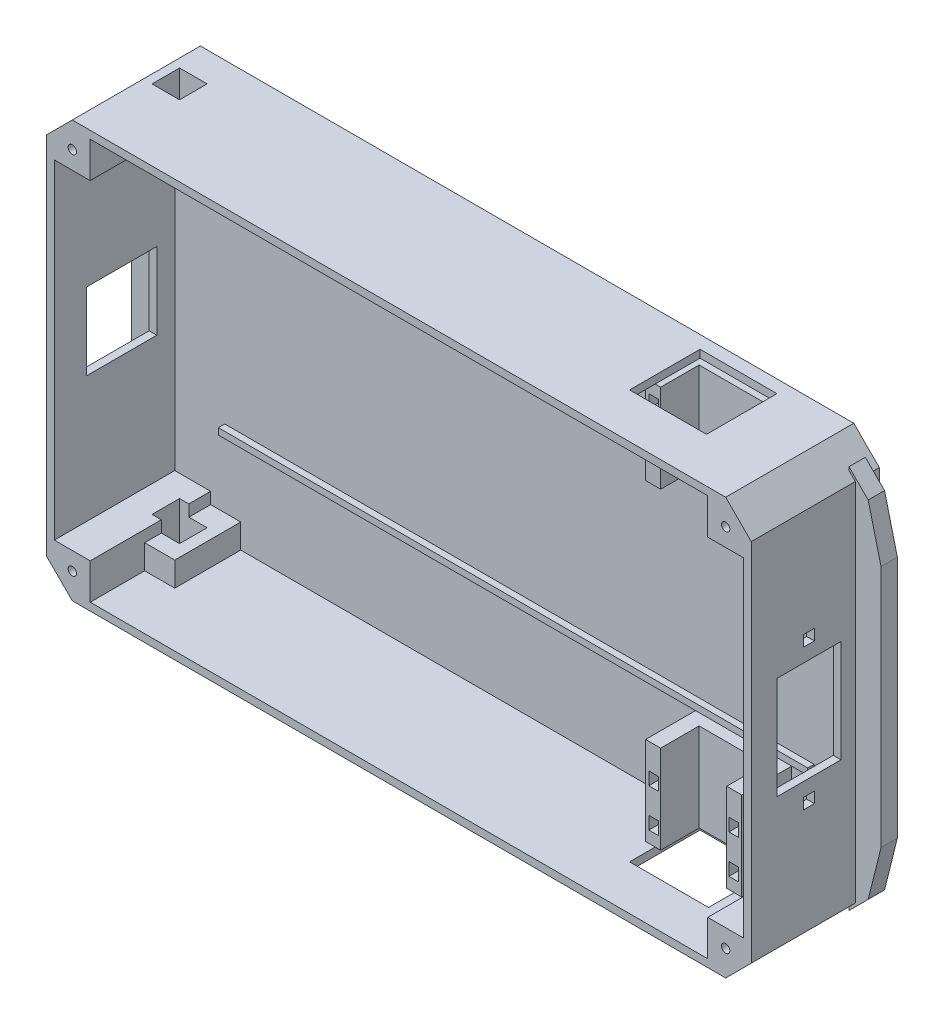
SolidWorks part; units mm, degrees
ref_plane "Front Plane" through (0, 0, 0) normal (0, 0, 1) x (1, 0, 0)
ref_plane "Top Plane" through (0, 0, 0) normal (0, 1, 0) x (1, 0, 0)
ref_plane "Right Plane" through (0, 0, 0) normal (1, 0, 0) x (0, 0, -1)
sketch "Sketch1" plane through (0, 0, 0) normal (0, 0, 1) x (1, 0, 0)
  line L0 (-102, -65) -> (102, -65)
  line L1 (102, -65) -> (110, -57)
  line L2 (110, -57) -> (110, 57)
  line L3 (110, 57) -> (102, 65)
  line L4 (102, 65) -> (-102, 65)
  line L5 (-102, 65) -> (-110, 57)
  line L6 (-110, 57) -> (-110, -57)
  line L7 (-110, -57) -> (-102, -65)
extrude "Faceted_Floor_220x130" add sketch "Sketch1" along normal blind 2.4 from offset 0
sketch "Sketch2" plane through (0, 0, 0) normal (0, 0, 1) x (1, 0, 0)
  line L0 (-102, -65) -> (102, -65)
  line L1 (102, -65) -> (110, -57)
  line L2 (110, -57) -> (110, 57)
  line L3 (110, 57) -> (102, 65)
  line L4 (102, 65) -> (-102, 65)
  line L5 (-102, 65) -> (-110, 57)
  line L6 (-110, 57) -> (-110, -57)
  line L7 (-110, -57) -> (-102, -65)
  line L8 (-102, -62.6) -> (102, -62.6)
  line L9 (102, -62.6) -> (107.6, -57)
  line L10 (107.6, -57) -> (107.6, 57)
  line L11 (107.6, 57) -> (102, 62.6)
  line L12 (102, 62.6) -> (-102, 62.6)
  line L13 (-102, 62.6) -> (-107.6, 57)
  line L14 (-107.6, 57) -> (-107.6, -57)
  line L15 (-107.6, -57) -> (-102, -62.6)
extrude "Faceted_Hollow_Walls_2p4" add sketch "Sketch2" along normal blind 37.6 from offset 2.4
sketch "Sketch3" plane through (0, 0, 0) normal (0, 0, 1) x (1, 0, 0)
  line L1 (-107.6, -62.6) -> (-96.4, -62.6)
  line L2 (-107.6, -62.6) -> (-107.6, -51.4)
  line L3 (-107.6, -51.4) -> (-96.4, -51.4)
  line L4 (-96.4, -62.6) -> (-96.4, -51.4)
extrude "Lid_Post_-1_-1" add sketch "Sketch3" along normal blind 37.6 from offset 2.4
sketch "Sketch4" plane through (0, 0, 0) normal (0, 0, 1) x (1, 0, 0)
  circle A0 centre (-102, -57) radius 1.3
extrude "M3_Pilot_-1_-1" cut sketch "Sketch4" along normal blind 14 from offset 27
sketch "Sketch5" plane through (0, 0, 0) normal (0, 0, 1) x (1, 0, 0)
  line L0 (-107.6, 57) -> (-107.6, -51.4) construction
  line L1 (-107.6, 51.4) -> (-96.4, 51.4)
  line L2 (-107.6, 51.4) -> (-107.6, 62.6)
  line L3 (-107.6, 62.6) -> (-96.4, 62.6)
  line L4 (-96.4, 51.4) -> (-96.4, 62.6)
  line L5 (102, 62.6) -> (-102, 62.6) construction
extrude "Lid_Post_-1_1" add sketch "Sketch5" along normal blind 37.6 from offset 2.4
sketch "Sketch6" plane through (0, 0, 0) normal (0, 0, 1) x (1, 0, 0)
  circle A0 centre (-102, 57) radius 1.3
extrude "M3_Pilot_-1_1" cut sketch "Sketch6" along normal blind 14 from offset 27
sketch "Sketch7" plane through (0, 0, 0) normal (0, 0, 1) x (1, 0, 0)
  line L0 (-96.4, -62.6) -> (102, -62.6) construction
  line L1 (96.4, -62.6) -> (107.6, -62.6)
  line L2 (96.4, -62.6) -> (96.4, -51.4)
  line L3 (96.4, -51.4) -> (107.6, -51.4)
  line L4 (107.6, -62.6) -> (107.6, -51.4)
  line L5 (107.6, -57) -> (107.6, 57) construction
extrude "Lid_Post_1_-1" add sketch "Sketch7" along normal blind 37.6 from offset 2.4
sketch "Sketch8" plane through (0, 0, 0) normal (0, 0, 1) x (1, 0, 0)
  circle A0 centre (102, -57) radius 1.3
extrude "M3_Pilot_1_-1" cut sketch "Sketch8" along normal blind 14 from offset 27
sketch "Sketch9" plane through (0, 0, 0) normal (0, 0, 1) x (1, 0, 0)
  line L1 (96.4, 51.4) -> (107.6, 51.4)
  line L2 (96.4, 51.4) -> (96.4, 62.6)
  line L3 (96.4, 62.6) -> (107.6, 62.6)
  line L4 (107.6, 51.4) -> (107.6, 62.6)
extrude "Lid_Post_1_1" add sketch "Sketch9" along normal blind 37.6 from offset 2.4
sketch "Sketch10" plane through (0, 0, 0) normal (0, 0, 1) x (1, 0, 0)
  circle A0 centre (102, 57) radius 1.3
extrude "M3_Pilot_1_1" cut sketch "Sketch10" along normal blind 14 from offset 27
sketch "Sketch11" plane through (0, 0, 0) normal (0, 0, 1) x (1, 0, 0)
  line L0 (-102, -65) -> (102, -65) construction
  line L1 (55, -65) -> (85, -65)
  line L2 (55, -65) -> (55, -35)
  line L3 (55, -35) -> (85, -35)
  line L4 (85, -65) -> (85, -35)
extrude "Motor_Saddle_Base_-1" add sketch "Sketch11" along normal blind 3.6 from offset 2.4
sketch "Sketch12" plane through (0, 0, 0) normal (0, 0, 1) x (1, 0, 0)
  line L0 (-102, -65) -> (102, -65) construction
  line L1 (55, -65) -> (59.7, -65)
  line L2 (55, -65) -> (55, -35)
  line L3 (55, -35) -> (59.7, -35)
  line L4 (59.7, -65) -> (59.7, -35)
  line L5 (85, -35) -> (55, -35) construction
extrude "Motor_Guide_A_-1" add sketch "Sketch12" along normal blind 12 from offset 6
sketch "Sketch13" plane through (0, 0, 0) normal (0, 0, 1) x (1, 0, 0)
  line L0 (-102, -65) -> (102, -65) construction
  line L1 (80.3, -65) -> (85, -65)
  line L2 (80.3, -65) -> (80.3, -35)
  line L3 (80.3, -35) -> (85, -35)
  line L4 (85, -65) -> (85, -35)
extrude "Motor_Guide_B_-1" add sketch "Sketch13" along normal blind 12 from offset 6
sketch "Sketch14" plane through (0, 0, 0) normal (0, 0, 1) x (1, 0, 0)
  line L1 (56, -47) -> (59, -47)
  line L2 (56, -47) -> (56, -43)
  line L3 (56, -43) -> (59, -43)
  line L4 (59, -47) -> (59, -43)
extrude "TieSlot_-1_56_43" cut sketch "Sketch14" along normal blind 19 from offset 0.1
sketch "Sketch15" plane through (0, 0, 0) normal (0, 0, 1) x (1, 0, 0)
  line L1 (81, -47) -> (84, -47)
  line L2 (81, -47) -> (81, -43)
  line L3 (81, -43) -> (84, -43)
  line L4 (84, -47) -> (84, -43)
extrude "TieSlot_-1_81_43" cut sketch "Sketch15" along normal blind 19 from offset 0.1
sketch "Sketch16" plane through (0, 0, 0) normal (0, 0, 1) x (1, 0, 0)
  line L1 (56, -59) -> (59, -59)
  line L2 (56, -59) -> (56, -55)
  line L3 (56, -55) -> (59, -55)
  line L4 (59, -59) -> (59, -55)
extrude "TieSlot_-1_56_55" cut sketch "Sketch16" along normal blind 19 from offset 0.1
sketch "Sketch17" plane through (0, 0, 0) normal (0, 0, 1) x (1, 0, 0)
  line L1 (81, -59) -> (84, -59)
  line L2 (81, -59) -> (81, -55)
  line L3 (81, -55) -> (84, -55)
  line L4 (84, -59) -> (84, -55)
extrude "TieSlot_-1_81_55" cut sketch "Sketch17" along normal blind 19 from offset 0.1
sketch "Sketch18" plane through (0, 0, 0) normal (0, 0, 1) x (1, 0, 0)
  line L0 (85, -62.6) -> (80.3, -62.6) construction
  line L1 (58, -66) -> (82.65, -66)
  line L2 (58, -66) -> (58, -62.6)
  line L3 (58, -62.6) -> (82.65, -62.6)
  line L4 (82.65, -66) -> (82.65, -62.6)
extrude "Motor_Side_Window_-1" cut sketch "Sketch18" along normal blind 22 from offset 4
sketch "Sketch19" plane through (0, 0, 0) normal (0, 0, 1) x (1, 0, 0)
  line L1 (-103, -65) -> (-87, -65)
  line L2 (-103, -65) -> (-103, -55)
  line L3 (-103, -55) -> (-87, -55)
  line L4 (-87, -65) -> (-87, -55)
extrude "Rear_Axle_Support_-1" add sketch "Sketch19" along normal blind 20.6 from offset 2.4
sketch "Sketch20" plane through (0, 0, 0) normal (0, 0, 1) x (1, 0, 0)
  line L1 (-99.3, -66) -> (-90.7, -66)
  line L2 (-99.3, -66) -> (-99.3, -51)
  line L3 (-99.3, -51) -> (-90.7, -51)
  line L4 (-90.7, -66) -> (-90.7, -51)
extrude "Rear_Printed_Axle_Clearance_8p6-1" cut sketch "Sketch20" along normal blind 8.6 from offset 9.2
sketch "Sketch21" plane through (0, 0, 0) normal (0, 0, 1) x (1, 0, 0)
  line L0 (102, 65) -> (-102, 65) construction
  line L1 (55, 35) -> (85, 35)
  line L2 (55, 35) -> (55, 65)
  line L3 (55, 65) -> (85, 65)
  line L4 (85, 35) -> (85, 65)
extrude "Motor_Saddle_Base_1" add sketch "Sketch21" along normal blind 3.6 from offset 2.4
sketch "Sketch22" plane through (0, 0, 0) normal (0, 0, 1) x (1, 0, 0)
  line L0 (102, 65) -> (-102, 65) construction
  line L1 (55, 35) -> (59.7, 35)
  line L2 (55, 35) -> (55, 65)
  line L3 (55, 65) -> (59.7, 65)
  line L4 (59.7, 35) -> (59.7, 65)
extrude "Motor_Guide_A_1" add sketch "Sketch22" along normal blind 12 from offset 6
sketch "Sketch23" plane through (0, 0, 0) normal (0, 0, 1) x (1, 0, 0)
  line L0 (59.7, 35) -> (85, 35) construction
  line L1 (80.3, 35) -> (85, 35)
  line L2 (80.3, 35) -> (80.3, 65)
  line L3 (80.3, 65) -> (85, 65)
  line L4 (85, 35) -> (85, 65)
  line L5 (102, 65) -> (-102, 65) construction
extrude "Motor_Guide_B_1" add sketch "Sketch23" along normal blind 12 from offset 6
sketch "Sketch24" plane through (0, 0, 0) normal (0, 0, 1) x (1, 0, 0)
  line L1 (56, 43) -> (59, 43)
  line L2 (56, 43) -> (56, 47)
  line L3 (56, 47) -> (59, 47)
  line L4 (59, 43) -> (59, 47)
extrude "TieSlot_1_56_43" cut sketch "Sketch24" along normal blind 19 from offset 0.1
sketch "Sketch25" plane through (0, 0, 0) normal (0, 0, 1) x (1, 0, 0)
  line L1 (81, 43) -> (84, 43)
  line L2 (81, 43) -> (81, 47)
  line L3 (81, 47) -> (84, 47)
  line L4 (84, 43) -> (84, 47)
extrude "TieSlot_1_81_43" cut sketch "Sketch25" along normal blind 19 from offset 0.1
sketch "Sketch26" plane through (0, 0, 0) normal (0, 0, 1) x (1, 0, 0)
  line L1 (56, 55) -> (59, 55)
  line L2 (56, 55) -> (56, 59)
  line L3 (56, 59) -> (59, 59)
  line L4 (59, 55) -> (59, 59)
extrude "TieSlot_1_56_55" cut sketch "Sketch26" along normal blind 19 from offset 0.1
sketch "Sketch27" plane through (0, 0, 0) normal (0, 0, 1) x (1, 0, 0)
  line L1 (81, 55) -> (84, 55)
  line L2 (81, 55) -> (81, 59)
  line L3 (81, 59) -> (84, 59)
  line L4 (84, 55) -> (84, 59)
extrude "TieSlot_1_81_55" cut sketch "Sketch27" along normal blind 19 from offset 0.1
sketch "Sketch28" plane through (0, 0, 0) normal (0, 0, 1) x (1, 0, 0)
  line L0 (96.4, 62.6) -> (-96.4, 62.6) construction
  line L1 (58, 62.6) -> (82, 62.6)
  line L2 (58, 62.6) -> (58, 66)
  line L3 (58, 66) -> (82, 66)
  line L4 (82, 62.6) -> (82, 66)
extrude "Motor_Side_Window_1" cut sketch "Sketch28" along normal blind 22 from offset 4
sketch "Sketch29" plane through (0, 0, 0) normal (0, 0, 1) x (1, 0, 0)
  line L0 (102, 65) -> (-102, 65) construction
  line L1 (-103, 55) -> (-87, 55)
  line L2 (-103, 55) -> (-103, 65)
  line L3 (-103, 65) -> (-87, 65)
  line L4 (-87, 55) -> (-87, 65)
extrude "Rear_Axle_Support_1" add sketch "Sketch29" along normal blind 20.6 from offset 2.4
sketch "Sketch30" plane through (0, 0, 0) normal (0, 0, 1) x (1, 0, 0)
  line L0 (-107.6, 51.4) -> (-96.4, 51.4) construction
  line L1 (-99.3, 51.4) -> (-90.7, 51.4)
  line L2 (-99.3, 51.4) -> (-99.3, 66)
  line L3 (-99.3, 66) -> (-90.7, 66)
  line L4 (-90.7, 51.4) -> (-90.7, 66)
extrude "Rear_Printed_Axle_Clearance_8p61" cut sketch "Sketch30" along normal blind 8.6 from offset 9.2
sketch "Sketch31" plane through (0, 0, 0) normal (0, 0, 1) x (1, 0, 0)
  line L0 (-107.6, 51.4) -> (-107.6, -51.4) construction
  line L1 (-111, -12) -> (-107.6, -12)
  line L2 (-111, -12) -> (-111, 12)
  line L3 (-111, 12) -> (-107.6, 12)
  line L4 (-107.6, -12) -> (-107.6, 12)
extrude "Rear_USB_Access_24x22" cut sketch "Sketch31" along normal blind 22 from offset 8
sketch "Sketch32" plane through (0, 0, 0) normal (0, 0, 1) x (1, 0, 0)
  line L0 (107.6, -51.4) -> (107.6, 51.4) construction
  line L1 (107.6, -16) -> (111, -16)
  line L2 (107.6, -16) -> (107.6, 16)
  line L3 (107.6, 16) -> (111, 16)
  line L4 (111, -16) -> (111, 16)
extrude "Front_ToF_Window_32x20" cut sketch "Sketch32" along normal blind 20 from offset 12
sketch "Sketch33" plane through (0, 0, 0) normal (0, 0, 1) x (1, 0, 0)
  line L0 (107.6, -51.4) -> (107.6, 51.4) construction
  line L1 (107.6, -23.7) -> (111, -23.7)
  line L2 (107.6, -23.7) -> (107.6, -20.3)
  line L3 (107.6, -20.3) -> (111, -20.3)
  line L4 (111, -23.7) -> (111, -20.3)
extrude "ToF_M3_Clearance_-1" cut sketch "Sketch33" along normal blind 3.4 from offset 20.3
sketch "Sketch34" plane through (0, 0, 0) normal (0, 0, 1) x (1, 0, 0)
  line L0 (107.6, -51.4) -> (107.6, 51.4) construction
  line L1 (107.6, 20.3) -> (111, 20.3)
  line L2 (107.6, 20.3) -> (107.6, 23.7)
  line L3 (107.6, 23.7) -> (111, 23.7)
  line L4 (111, 20.3) -> (111, 23.7)
extrude "ToF_M3_Clearance_1" cut sketch "Sketch34" along normal blind 3.4 from offset 20.3
sketch "Sketch35" plane through (0, 0, 0) normal (0, 0, 1) x (1, 0, 0)
  line L1 (-92, -33) -> (92, -33)
  line L2 (-92, -33) -> (-92, -31)
  line L3 (-92, -31) -> (92, -31)
  line L4 (92, -33) -> (92, -31)
extrude "Breadboard_Left_Guide" add sketch "Sketch35" along normal blind 2 from offset 2.4
sketch "Sketch36" plane through (0, 0, 0) normal (0, 0, 1) x (1, 0, 0)
  line L1 (-92, 31) -> (92, 31)
  line L2 (-92, 31) -> (-92, 33)
  line L3 (-92, 33) -> (92, 33)
  line L4 (92, 31) -> (92, 33)
extrude "Breadboard_Right_Guide" add sketch "Sketch36" along normal blind 2 from offset 2.4
sketch "Sketch37" plane through (0, 0, 0) normal (0, 0, 1) x (1, 0, 0)
  line L0 (-102, -65) -> (-110, -57)
  line L1 (-110, -57) -> (-110, -65)
  line L2 (-110, -65) -> (-102, -65)
extrude "Outer_Corner_Trim_-1_-1" cut sketch "Sketch37" along normal blind 40.2 from offset 0.1
sketch "Sketch38" plane through (0, 0, 0) normal (0, 0, 1) x (1, 0, 0)
  line L0 (-102, 65) -> (-110, 57)
  line L1 (-110, 57) -> (-110, 65)
  line L2 (-110, 65) -> (-102, 65)
extrude "Outer_Corner_Trim_-1_1" cut sketch "Sketch38" along normal blind 40.2 from offset 0.1
sketch "Sketch39" plane through (0, 0, 0) normal (0, 0, 1) x (1, 0, 0)
  line L0 (102, -65) -> (110, -57)
  line L1 (110, -57) -> (110, -65)
  line L2 (110, -65) -> (102, -65)
extrude "Outer_Corner_Trim_1_-1" cut sketch "Sketch39" along normal blind 40.2 from offset 0.1
sketch "Sketch40" plane through (0, 0, 0) normal (0, 0, 1) x (1, 0, 0)
  line L0 (102, 65) -> (110, 57)
  line L1 (110, 57) -> (110, 65)
  line L2 (110, 65) -> (102, 65)
extrude "Outer_Corner_Trim_1_1" cut sketch "Sketch40" along normal blind 40.2 from offset 0.1
sketch "Sketch41" plane through (0, 0, 0) normal (0, 0, 1) x (1, 0, 0)
  line L0 (108, -60) -> (114, -54)
  line L1 (114, -54) -> (118, -38)
  line L2 (118, -38) -> (118, 38)
  line L3 (118, 38) -> (114, 54)
  line L4 (114, 54) -> (108, 60)
  line L5 (108, 60) -> (108, -60)
extrude "Angled_Front_Bumper" add sketch "Sketch41" along normal blind 5.1 from offset 2.4
sketch "Sketch42" plane through (0, 0, 0) normal (0, 0, 1) x (1, 0, 0)
  line L0 (-107.6, -45) -> (-112, -45)
  line L1 (-107.6, 51.4) -> (-107.6, -51.4) construction
  line L2 (-112, -45) -> (-116, -39)
  line L3 (-116, -39) -> (-116, 39)
  line L4 (-116, 39) -> (-112, 45)
  line L5 (-112, 45) -> (-107.6, 45)
  line L6 (-107.6, 45) -> (-107.6, -45)
extrude "Angled_Rear_Bumper" add sketch "Sketch42" along normal blind 5.1 from offset 2.4
